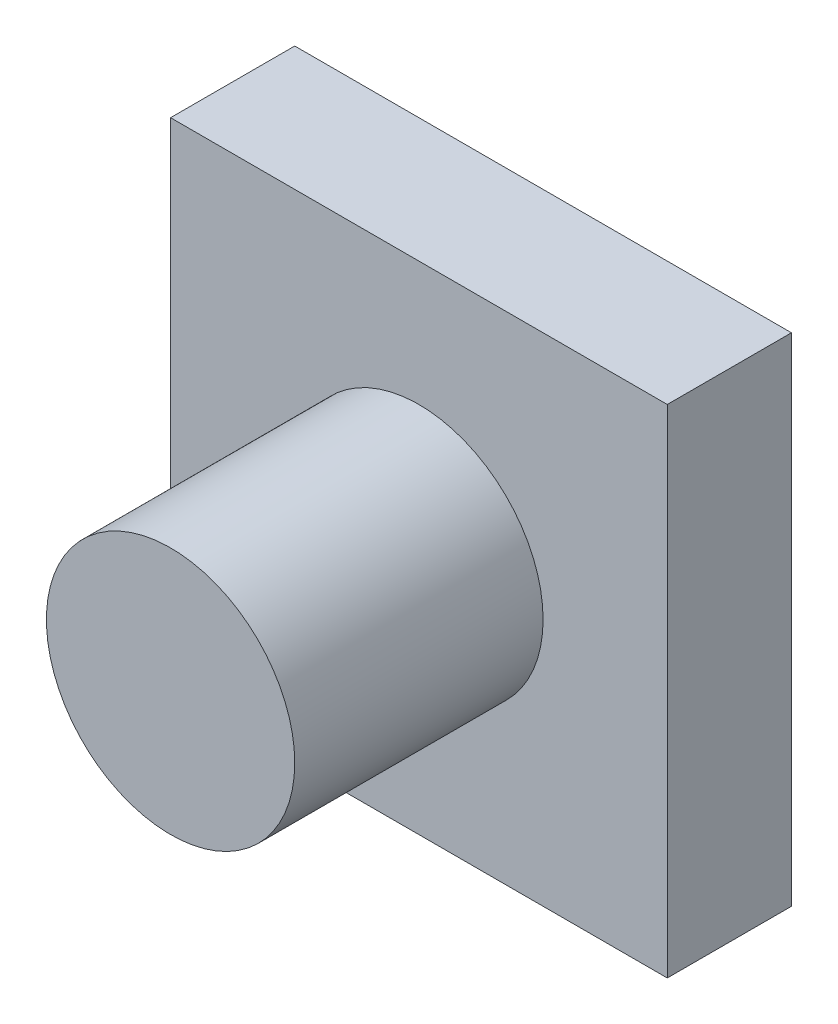
SolidWorks part; units mm, degrees
ref_plane "Front Plane" through (0, 0, 0) normal (0, 0, 1) x (1, 0, 0)
ref_plane "Top Plane" through (0, 0, 0) normal (0, 1, 0) x (1, 0, 0)
ref_plane "Right Plane" through (0, 0, 0) normal (1, 0, 0) x (0, 0, -1)
sketch "Sketch1" plane through (0, 0, 0) normal (0, 0, 1) x (1, 0, 0)
  line L1 (-13.289, 15.2159) -> (26.711, 15.2159)
  line L2 (-13.289, 15.2159) -> (-13.289, -24.7841)
  line L3 (-13.289, -24.7841) -> (26.711, -24.7841)
  line L4 (26.711, 15.2159) -> (26.711, -24.7841)
  dimension "D1" = 40
  dimension "D2" = 40
extrude "Boss-Extrude1" add sketch "Sketch1" along normal blind 10
sketch "Sketch3" plane through (0, 0, 10) normal (0, 0, 1) x (1, 0, 0)
  circle A0 centre (6.711, -4.7841) radius 10
  dimension "D1" = 20
extrude "Boss-Extrude2" add sketch "Sketch3" along normal blind 20
